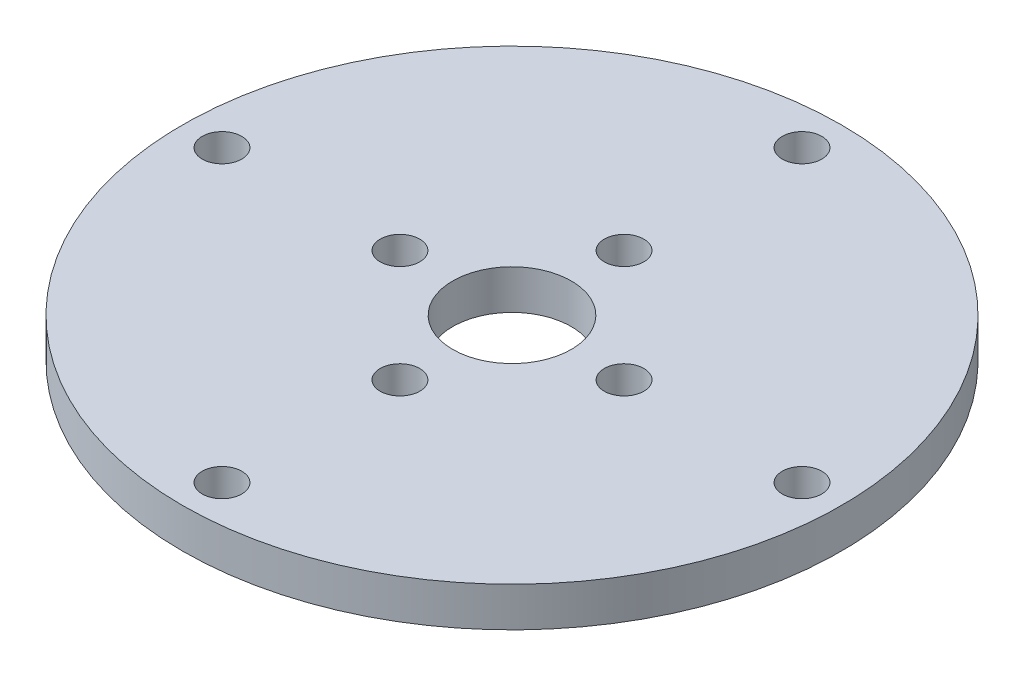
SolidWorks part; units mm, degrees
ref_plane "Front Plane" through (0, 0, 0) normal (0, 0, 1) x (1, 0, 0)
ref_plane "Top Plane" through (0, 0, 0) normal (0, 1, 0) x (1, 0, 0)
ref_plane "Right Plane" through (0, 0, 0) normal (1, 0, 0) x (0, 0, -1)
sketch "Sketch1" plane through (0, 0, 0) normal (0, 1, 0) x (1, 0, 0)
  circle A0 centre (0, 0) radius 25
  circle A1 centre (0, 0) radius 4.5
  dimension "D1" = 50
  dimension "D2" = 9
extrude "Boss-Extrude1" add sketch "Sketch1" along normal blind 3
sketch "Sketch2" plane through (0, 3, 0) normal (0, 1, 0) x (1, 0, 0)
  circle A0 centre (0, 0) radius 8.5 construction
  circle A1 centre (0, 8.5) radius 1.5
  dimension "D1" = 17
  dimension "D2" = 3
extrude "Cut-Extrude1" cut sketch "Sketch2" against normal through all
pattern_circular "CirPattern1" count 4 over 360 about axis through (0, 0, 0) along (0, 1, 0) of "Cut-Extrude1"
sketch "Sketch3" plane through (0, 3, 0) normal (0, 1, 0) x (1, 0, 0)
  circle A0 centre (0, 0) radius 22 construction
  circle A1 centre (0, 22) radius 1.5
  point P5 (8.6308, 20.2364)
  point P6 (0, 0)
  dimension "D1" = 44
  dimension "D2" = 3
extrude "Cut-Extrude3" cut sketch "Sketch3" against normal through all contours A1 | A0
pattern_circular "CirPattern2" count 4 over 360 about axis through (0, 0, 0) along (0, 1, 0) of "Cut-Extrude3"
